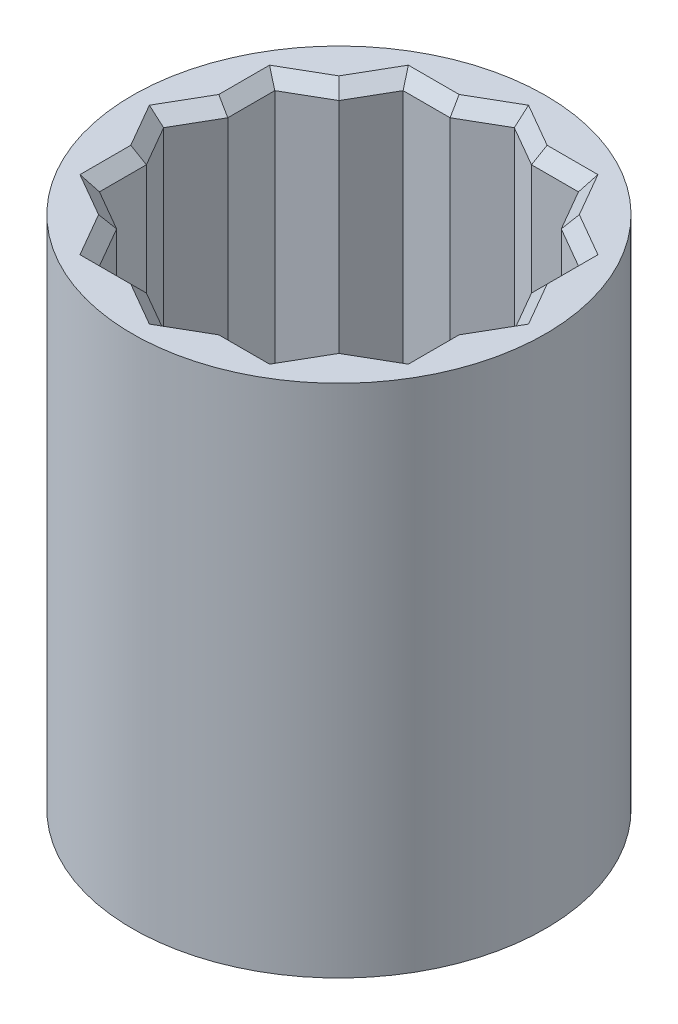
SolidWorks part; units mm, degrees
ref_plane "Front Plane" through (0, 0, 0) normal (0, 0, 1) x (1, 0, 0)
ref_plane "Top Plane" through (0, 0, 0) normal (0, 1, 0) x (1, 0, 0)
ref_plane "Right Plane" through (0, 0, 0) normal (1, 0, 0) x (0, 0, -1)
sketch "Sketch1" plane through (0, 0, 0) normal (0, 1, 0) x (1, 0, 0)
  circle A0 centre (0, 0) radius 9.779
  dimension "Socket_Diameter" = 19.558
extrude "Boss-Extrude1" add sketch "Sketch1" along normal blind 24.384
sketch "Sketch2" plane through (0, 0, 0) normal (0, -1, 0) x (1, 0, 0)
  line L1 (-4.826, 4.826) -> (4.826, 4.826)
  line L2 (-4.826, 4.826) -> (-4.826, -4.826)
  line L3 (-4.826, -4.826) -> (4.826, -4.826)
  line L4 (4.826, 4.826) -> (4.826, -4.826)
  line L5 (-4.826, 4.826) -> (4.826, -4.826) construction
  line L6 (-4.826, -4.826) -> (4.826, 4.826) construction
  point P0 (0, 0)
  dimension "D1" = 9.652
  dimension "D2" = 9.652
extrude "Cut-Extrude1" cut sketch "Sketch2" against normal blind 11.43
sketch "Sketch3" plane through (0, 24.384, 0) normal (0, 1, 0) x (1, 0, 0)
  line L1 (8.3002, 0) -> (4.1501, 7.1882)
  line L2 (4.1501, 7.1882) -> (-4.1501, 7.1882)
  line L3 (-4.1501, 7.1882) -> (-8.3002, 0)
  line L4 (-8.3002, 0) -> (-4.1501, -7.1882)
  line L5 (-4.1501, -7.1882) -> (4.1501, -7.1882)
  line L6 (4.1501, -7.1882) -> (8.3002, 0)
  circle A0 centre (0, 0) radius 7.1882 construction
  dimension "D1" = 14.3764
extrude "Cut-Extrude2" cut sketch "Sketch3" against normal up to surface (12.954 mm away) up to face at (0, 11.43, 0)
pattern_circular "CirPattern1" count 2 every 30 about axis through (0, 0, 0) along (0, 1, 0) of "Cut-Extrude2"
chamfer "Chamfer1" distance 0.5842 24 edges at (7.1882, 24.384, -3.0381) (7.1882, 24.384, 3.0381) (7.7442, 24.384, -0.963) (7.7442, 24.384, 0.963) (6.2252, 24.384, 4.7061) (0.963, 24.384, 7.7442) (4.7061, 24.384, 6.2252) (3.0381, 24.384, 7.1882) (-0.963, 24.384, 7.7442) (-6.2252, 24.384, 4.7061) (-3.0381, 24.384, 7.1882) (-4.7061, 24.384, 6.2252) (-7.1882, 24.384, 3.0381) (-7.1882, 24.384, -3.0381) (-7.7442, 24.384, 0.963) (-7.7442, 24.384, -0.963) (0.963, 24.384, -7.7442) (6.2252, 24.384, -4.7061) (4.7061, 24.384, -6.2252) (3.0381, 24.384, -7.1882) (-6.2252, 24.384, -4.7061) (-0.963, 24.384, -7.7442) (-3.0381, 24.384, -7.1882) (-4.7061, 24.384, -6.2252)
